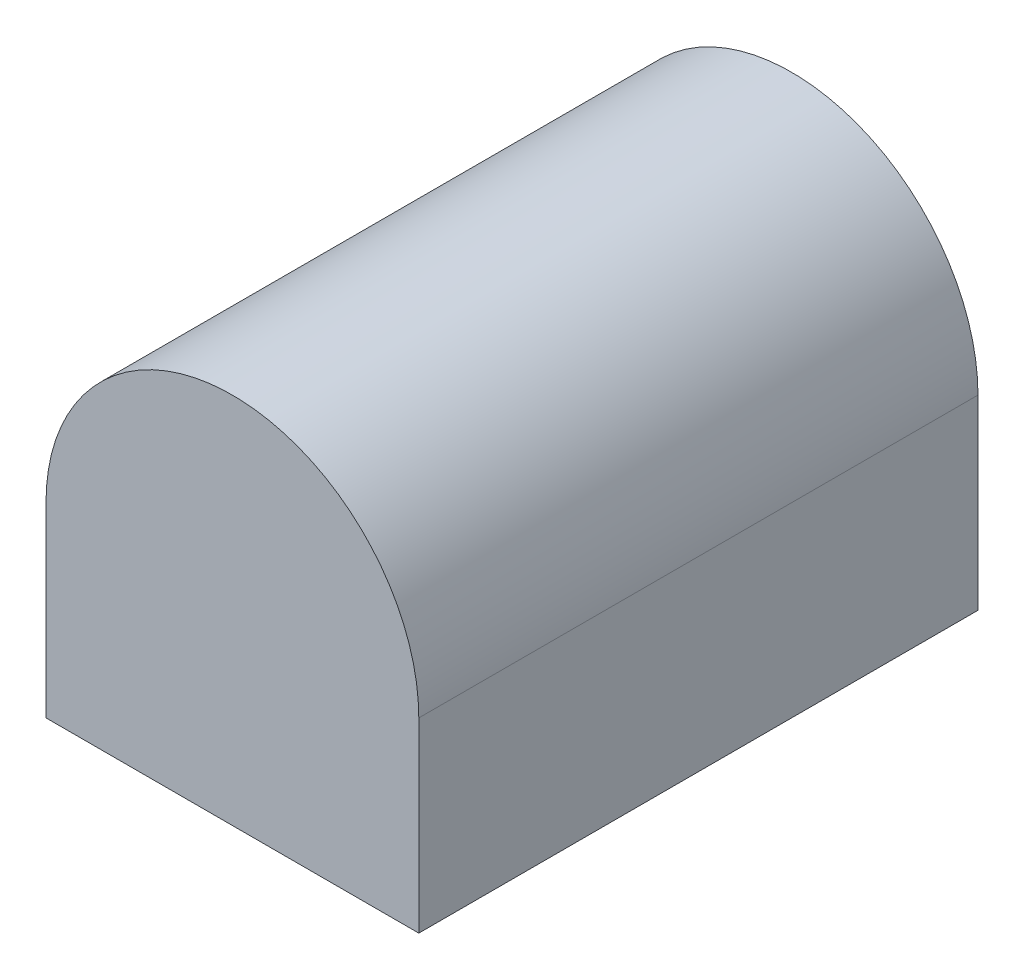
SolidWorks part; units mm, degrees
ref_plane "Front Plane" through (0, 0, 0) normal (0, 0, 1) x (1, 0, 0)
ref_plane "Top Plane" through (0, 0, 0) normal (0, 1, 0) x (1, 0, 0)
ref_plane "Right Plane" through (0, 0, 0) normal (1, 0, 0) x (0, 0, -1)
sketch "Sketch1" plane through (0, 0, 0) normal (0, 0, 1) x (1, 0, 0)
  line L0 (-1, 0) -> (1, 0)
  line L1 (-1, 0) -> (-1, 1)
  line L3 (1, 1) -> (1, 0)
  line L4 (0, 2.6569) -> (0, -1.3603) construction
  arc A0 (1, 1) -> (-1, 1) centre (0, 1) ccw
  dimension "D2" = 2
  dimension "D1" = 1
  dimension "D3" = 2
extrude "Boss-Extrude1" add sketch "Sketch1" along normal mid plane 3
